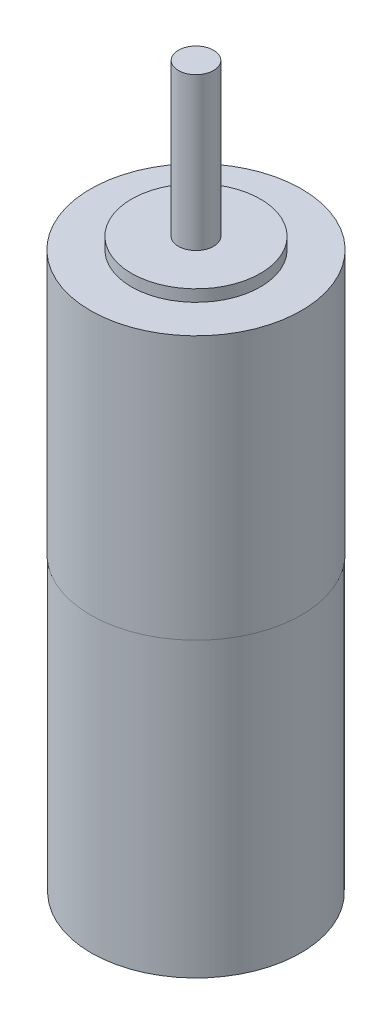
SolidWorks part; units mm, degrees
ref_plane "前视基准面" through (0, 0, 0) normal (0, 0, 1) x (1, 0, 0)
ref_plane "上视基准面" through (0, 0, 0) normal (0, 1, 0) x (1, 0, 0)
ref_plane "右视基准面" through (0, 0, 0) normal (1, 0, 0) x (0, 0, -1)
sketch "草图1" plane through (0, 0, 0) normal (0, 1, 0) x (1, 0, 0)
  circle A0 centre (0, 0) radius 17.9
  dimension "D1" = 35.8
extrude "凸台-拉伸1" add sketch "草图1" along normal blind 50
sketch "草图3" plane through (0, 50, 0) normal (0, 1, 0) x (1, 0, 0)
  circle A0 centre (0, 0) radius 18
  dimension "D1" = 36
extrude "凸台-拉伸2" add sketch "草图3" along normal blind 45
sketch "草图4" plane through (0, 95, 0) normal (0, 1, 0) x (1, 0, 0)
  circle A0 centre (0, 0) radius 11
  dimension "D1" = 22
extrude "凸台-拉伸3" add sketch "草图4" along normal blind 2
sketch "草图5" plane through (0, 97, 0) normal (0, 1, 0) x (1, 0, 0)
  circle A0 centre (0, 0) radius 3
  dimension "D1" = 6
extrude "凸台-拉伸4" add sketch "草图5" along normal blind 26
